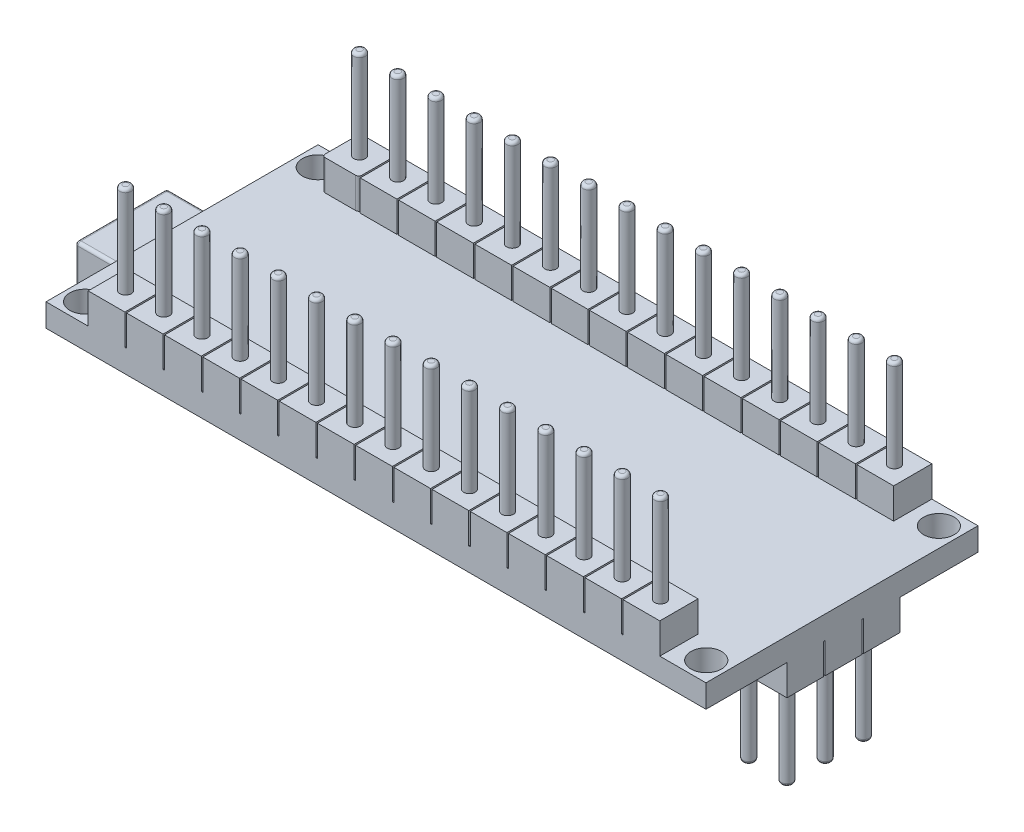
SolidWorks part; units mm, degrees
ref_plane "Front Plane" through (0, 0, 0) normal (0, 0, 1) x (1, 0, 0)
ref_plane "Top Plane" through (0, 0, 0) normal (0, 1, 0) x (1, 0, 0)
ref_plane "Right Plane" through (0, 0, 0) normal (1, 0, 0) x (0, 0, -1)
sketch "Sketch1" plane through (0, 0, 0) normal (0, 1, 0) x (1, 0, 0)
  line L1 (21.59, -8.9) -> (-21.59, -8.9)
  line L2 (21.59, -8.9) -> (21.59, 8.9)
  line L3 (21.59, 8.9) -> (-21.59, 8.9)
  line L4 (-21.59, -8.9) -> (-21.59, 8.9)
  line L5 (21.59, -8.9) -> (-21.59, 8.9) construction
  line L6 (21.59, 8.9) -> (-21.59, -8.9) construction
  point P0 (0, 0)
  dimension "D1" = 17.8
  dimension "D2" = 43.18
extrude "Boss-Extrude1" add sketch "Sketch1" along normal blind 1.5
sketch "Sketch5" plane through (0, 1.5, 0) normal (0, 1, 0) x (1, 0, 0)
  line L0 (21.59, 8.9) -> (-21.59, 8.9) construction
  line L1 (-21.59, 8.9) -> (-21.59, -8.9) construction
  line L2 (0, 8.9) -> (0, -8.9) construction
  line L3 (-21.59, -8.9) -> (21.59, -8.9) construction
  line L4 (21.59, 0) -> (-29.5736, 0) construction
  line L5 (21.59, -8.9) -> (21.59, 8.9) construction
  circle A0 centre (-20.32, 7.61) radius 1
  circle A1 centre (20.32, 7.61) radius 1
  circle A2 centre (20.32, -7.61) radius 1
  circle A3 centre (-20.32, -7.61) radius 1
  dimension "D3" = 2
  dimension "D1" = 1.29
  dimension "D2" = 1.27
extrude "Cut-Extrude2" cut sketch "Sketch5" against normal blind 6
sketch "Sketch6" plane through (0, 1.5, 0) normal (0, 1, 0) x (1, 0, 0)
  line L0 (21.59, 8.9) -> (-21.59, 8.9) construction
  line L1 (-18.83, 8.9) -> (-16.43, 8.9)
  line L2 (-18.83, 8.9) -> (-18.83, 6.4)
  line L3 (-18.83, 6.4) -> (-16.43, 6.4)
  line L4 (-16.43, 8.9) -> (-16.43, 6.4)
  line L5 (-18.83, 8.9) -> (-16.43, 6.4) construction
  line L6 (-18.83, 6.4) -> (-16.43, 8.9) construction
  line L7 (-21.59, 8.9) -> (-21.59, -8.9) construction
  line L8 (-16.33, 8.9) -> (-13.93, 8.9)
  line L9 (-16.33, 8.9) -> (-16.33, 6.4)
  line L10 (-16.33, 6.4) -> (-13.93, 6.4)
  line L11 (-13.93, 8.9) -> (-13.93, 6.4)
  line L12 (-13.83, 8.9) -> (-11.43, 8.9)
  line L13 (-13.83, 8.9) -> (-13.83, 6.4)
  line L14 (-13.83, 6.4) -> (-11.43, 6.4)
  line L15 (-11.43, 8.9) -> (-11.43, 6.4)
  line L16 (-11.33, 8.9) -> (-8.93, 8.9)
  line L17 (-11.33, 8.9) -> (-11.33, 6.4)
  line L18 (-11.33, 6.4) -> (-8.93, 6.4)
  line L19 (-8.93, 8.9) -> (-8.93, 6.4)
  line L20 (-8.83, 8.9) -> (-6.43, 8.9)
  line L21 (-8.83, 8.9) -> (-8.83, 6.4)
  line L22 (-8.83, 6.4) -> (-6.43, 6.4)
  line L23 (-6.43, 8.9) -> (-6.43, 6.4)
  line L24 (-6.33, 8.9) -> (-3.93, 8.9)
  line L25 (-6.33, 8.9) -> (-6.33, 6.4)
  line L26 (-6.33, 6.4) -> (-3.93, 6.4)
  line L27 (-3.93, 8.9) -> (-3.93, 6.4)
  line L28 (-3.83, 8.9) -> (-1.43, 8.9)
  line L29 (-3.83, 8.9) -> (-3.83, 6.4)
  line L30 (-3.83, 6.4) -> (-1.43, 6.4)
  line L31 (-1.43, 8.9) -> (-1.43, 6.4)
  line L32 (-1.33, 8.9) -> (1.07, 8.9)
  line L33 (-1.33, 8.9) -> (-1.33, 6.4)
  line L34 (-1.33, 6.4) -> (1.07, 6.4)
  line L35 (1.07, 8.9) -> (1.07, 6.4)
  line L36 (1.17, 8.9) -> (3.57, 8.9)
  line L37 (1.17, 8.9) -> (1.17, 6.4)
  line L38 (1.17, 6.4) -> (3.57, 6.4)
  line L39 (3.57, 8.9) -> (3.57, 6.4)
  line L40 (3.67, 8.9) -> (6.07, 8.9)
  line L41 (3.67, 8.9) -> (3.67, 6.4)
  line L42 (3.67, 6.4) -> (6.07, 6.4)
  line L43 (6.07, 8.9) -> (6.07, 6.4)
  line L44 (6.17, 8.9) -> (8.57, 8.9)
  line L45 (6.17, 8.9) -> (6.17, 6.4)
  line L46 (6.17, 6.4) -> (8.57, 6.4)
  line L47 (8.57, 8.9) -> (8.57, 6.4)
  line L48 (8.67, 8.9) -> (11.07, 8.9)
  line L49 (8.67, 8.9) -> (8.67, 6.4)
  line L50 (8.67, 6.4) -> (11.07, 6.4)
  line L51 (11.07, 8.9) -> (11.07, 6.4)
  line L52 (11.17, 8.9) -> (13.57, 8.9)
  line L53 (11.17, 8.9) -> (11.17, 6.4)
  line L54 (11.17, 6.4) -> (13.57, 6.4)
  line L55 (13.57, 8.9) -> (13.57, 6.4)
  line L56 (13.67, 8.9) -> (16.07, 8.9)
  line L57 (13.67, 8.9) -> (13.67, 6.4)
  line L58 (13.67, 6.4) -> (16.07, 6.4)
  line L59 (16.07, 8.9) -> (16.07, 6.4)
  line L60 (16.17, 8.9) -> (18.57, 8.9)
  line L61 (16.17, 8.9) -> (16.17, 6.4)
  line L62 (16.17, 6.4) -> (18.57, 6.4)
  line L63 (18.57, 8.9) -> (18.57, 6.4)
  line L64 (0, 0) -> (21.59, 0) construction
  line L65 (21.59, -8.9) -> (21.59, 8.9) construction
  line L66 (-18.83, -6.4) -> (-16.43, -8.9) construction
  line L67 (-18.83, -8.9) -> (-16.43, -6.4) construction
  line L68 (18.57, -8.9) -> (18.57, -6.4)
  line L69 (16.17, -6.4) -> (18.57, -6.4)
  line L70 (16.17, -8.9) -> (16.17, -6.4)
  line L71 (16.17, -8.9) -> (18.57, -8.9)
  line L72 (16.07, -8.9) -> (16.07, -6.4)
  line L73 (13.67, -6.4) -> (16.07, -6.4)
  line L74 (13.67, -8.9) -> (13.67, -6.4)
  line L75 (13.67, -8.9) -> (16.07, -8.9)
  line L76 (13.57, -8.9) -> (13.57, -6.4)
  line L77 (11.17, -6.4) -> (13.57, -6.4)
  line L78 (11.17, -8.9) -> (11.17, -6.4)
  line L79 (11.17, -8.9) -> (13.57, -8.9)
  line L80 (11.07, -8.9) -> (11.07, -6.4)
  line L81 (8.67, -6.4) -> (11.07, -6.4)
  line L82 (8.67, -8.9) -> (8.67, -6.4)
  line L83 (8.67, -8.9) -> (11.07, -8.9)
  line L84 (8.57, -8.9) -> (8.57, -6.4)
  line L85 (6.17, -6.4) -> (8.57, -6.4)
  line L86 (6.17, -8.9) -> (6.17, -6.4)
  line L87 (6.17, -8.9) -> (8.57, -8.9)
  line L88 (6.07, -8.9) -> (6.07, -6.4)
  line L89 (3.67, -6.4) -> (6.07, -6.4)
  line L90 (3.67, -8.9) -> (3.67, -6.4)
  line L91 (3.67, -8.9) -> (6.07, -8.9)
  line L92 (3.57, -8.9) -> (3.57, -6.4)
  line L93 (1.17, -6.4) -> (3.57, -6.4)
  line L94 (1.17, -8.9) -> (1.17, -6.4)
  line L95 (1.17, -8.9) -> (3.57, -8.9)
  line L96 (1.07, -8.9) -> (1.07, -6.4)
  line L97 (-1.33, -6.4) -> (1.07, -6.4)
  line L98 (-1.33, -8.9) -> (-1.33, -6.4)
  line L99 (-1.33, -8.9) -> (1.07, -8.9)
  line L100 (-1.43, -8.9) -> (-1.43, -6.4)
  line L101 (-3.83, -6.4) -> (-1.43, -6.4)
  line L102 (-3.83, -8.9) -> (-3.83, -6.4)
  line L103 (-3.83, -8.9) -> (-1.43, -8.9)
  line L104 (-3.93, -8.9) -> (-3.93, -6.4)
  line L105 (-6.33, -6.4) -> (-3.93, -6.4)
  line L106 (-6.33, -8.9) -> (-6.33, -6.4)
  line L107 (-6.33, -8.9) -> (-3.93, -8.9)
  line L108 (-6.43, -8.9) -> (-6.43, -6.4)
  line L109 (-8.83, -6.4) -> (-6.43, -6.4)
  line L110 (-8.83, -8.9) -> (-8.83, -6.4)
  line L111 (-8.83, -8.9) -> (-6.43, -8.9)
  line L112 (-8.93, -8.9) -> (-8.93, -6.4)
  line L113 (-11.33, -6.4) -> (-8.93, -6.4)
  line L114 (-11.33, -8.9) -> (-11.33, -6.4)
  line L115 (-11.33, -8.9) -> (-8.93, -8.9)
  line L116 (-11.43, -8.9) -> (-11.43, -6.4)
  line L117 (-13.83, -6.4) -> (-11.43, -6.4)
  line L118 (-13.83, -8.9) -> (-13.83, -6.4)
  line L119 (-13.83, -8.9) -> (-11.43, -8.9)
  line L120 (-13.93, -8.9) -> (-13.93, -6.4)
  line L121 (-16.33, -6.4) -> (-13.93, -6.4)
  line L122 (-16.33, -8.9) -> (-16.33, -6.4)
  line L123 (-16.33, -8.9) -> (-13.93, -8.9)
  line L124 (-16.43, -8.9) -> (-16.43, -6.4)
  line L125 (-18.83, -6.4) -> (-16.43, -6.4)
  line L126 (-18.83, -8.9) -> (-18.83, -6.4)
  line L127 (-18.83, -8.9) -> (-16.43, -8.9)
  point P0 (-17.63, 7.65)
  point P130 (-17.63, -7.65)
  dimension "D1" = 2.4
  dimension "D2" = 2.5
  dimension "D3" = 0
  dimension "D4" = 2.76
  dimension "D5" = 15
extrude "Boss-Extrude3" add sketch "Sketch6" along normal blind 2
sketch "Sketch7" plane through (0, 3.5, 0) normal (0, 1, 0) x (1, 0, 0)
  line L0 (-18.83, 8.9) -> (-18.83, 6.4) construction
  line L1 (-16.43, 8.9) -> (-18.83, 8.9) construction
  line L2 (0, 0) -> (21.1488, 0) construction
  circle A0 centre (-17.63, 7.6546) radius 0.375
  circle A1 centre (-15.13, 7.6546) radius 0.375
  circle A2 centre (-12.63, 7.6546) radius 0.375
  circle A3 centre (-10.13, 7.6546) radius 0.375
  circle A4 centre (-7.63, 7.6546) radius 0.375
  circle A5 centre (-5.13, 7.6546) radius 0.375
  circle A6 centre (-2.63, 7.6546) radius 0.375
  circle A7 centre (-0.13, 7.6546) radius 0.375
  circle A8 centre (2.37, 7.6546) radius 0.375
  circle A9 centre (4.87, 7.6546) radius 0.375
  circle A10 centre (7.37, 7.6546) radius 0.375
  circle A11 centre (9.87, 7.6546) radius 0.375
  circle A12 centre (12.37, 7.6546) radius 0.375
  circle A13 centre (14.87, 7.6546) radius 0.375
  circle A14 centre (17.37, 7.6546) radius 0.375
  circle A15 centre (17.37, -7.6546) radius 0.375
  circle A16 centre (14.87, -7.6546) radius 0.375
  circle A17 centre (12.37, -7.6546) radius 0.375
  circle A18 centre (9.87, -7.6546) radius 0.375
  circle A19 centre (7.37, -7.6546) radius 0.375
  circle A20 centre (4.87, -7.6546) radius 0.375
  circle A21 centre (2.37, -7.6546) radius 0.375
  circle A22 centre (-0.13, -7.6546) radius 0.375
  circle A23 centre (-2.63, -7.6546) radius 0.375
  circle A24 centre (-5.13, -7.6546) radius 0.375
  circle A25 centre (-7.63, -7.6546) radius 0.375
  circle A26 centre (-10.13, -7.6546) radius 0.375
  circle A27 centre (-12.63, -7.6546) radius 0.375
  circle A28 centre (-15.13, -7.6546) radius 0.375
  circle A29 centre (-17.63, -7.6546) radius 0.375
  point P2 (-18.83, 7.65)
  dimension "D1" = 0.75
  dimension "D3" = 1.2454
  dimension "D2" = 1.2
  dimension "D4" = 15
extrude "Boss-Extrude4" add sketch "Sketch7" along normal blind 6
fillet "Fillet5" radius 0.2 30 edges at (-15.13, 9.5, 7.2796) (-5.13, 9.5, -7.2796) (-7.63, 9.5, -7.2796) (-17.63, 9.5, 7.2796) (-12.63, 9.5, 7.2796) (-10.13, 9.5, 7.2796) (-7.63, 9.5, 7.2796) (-5.13, 9.5, 7.2796) (-2.63, 9.5, 7.2796) (-0.13, 9.5, 7.2796) (2.37, 9.5, 7.2796) (4.87, 9.5, 7.2796) (7.37, 9.5, 7.2796) (9.87, 9.5, 7.2796) (12.37, 9.5, 7.2796) (14.87, 9.5, 7.2796) (17.37, 9.5, 7.2796) (17.37, 9.5, -7.2796) (14.87, 9.5, -7.2796) (12.37, 9.5, -7.2796) (9.87, 9.5, -7.2796) (7.37, 9.5, -7.2796) (4.87, 9.5, -7.2796) (2.37, 9.5, -7.2796) (-0.13, 9.5, -7.2796) (-2.63, 9.5, -7.2796) (-10.13, 9.5, -7.2796) (-12.63, 9.5, -7.2796) (-15.13, 9.5, -7.2796) (-17.63, 9.5, -7.2796)
sketch "Sketch8" plane through (0, 0, 0) normal (0, -1, 0) x (1, 0, 0)
  line L0 (-21.59, -8.9) -> (-21.59, 8.9) construction
  line L1 (-17.59, -3) -> (-25.59, -3)
  line L2 (-17.59, -3) -> (-17.59, 3)
  line L3 (-17.59, 3) -> (-25.59, 3)
  line L4 (-25.59, -3) -> (-25.59, 3)
  line L5 (-17.59, -3) -> (-25.59, 3) construction
  line L6 (-17.59, 3) -> (-25.59, -3) construction
  point P0 (-21.59, 0)
  dimension "D1" = 6
  dimension "D2" = 8
extrude "Boss-Extrude5" add sketch "Sketch8" along normal blind 6
sketch "Sketch9" plane through (-25.59, 0, 0) normal (-1, 0, 0) x (0, 0, 1)
  line L0 (2.5, -0.5) -> (-2.5, -0.5)
  line L1 (-2.5, -0.5) -> (-2.5, -5.5)
  line L2 (-2.5, -5.5) -> (2.5, -5.5)
  line L3 (2.5, -5.5) -> (2.5, -0.5)
  line L4 (3, 0) -> (-3, 0)
  line L5 (-3, 0) -> (-3, -6)
  line L6 (-3, -6) -> (3, -6)
  line L7 (3, -6) -> (3, 0)
  line L8 (3, 0) -> (-3, 0)
  line L9 (-3, 0) -> (-3, -6)
  line L10 (-3, -6) -> (3, -6)
  line L11 (3, -6) -> (3, 0)
  dimension "D1" = 0
  dimension "D2" = 0.5
extrude "Cut-Extrude3" cut sketch "Sketch9" against normal blind 6 contours L2 L3 L0 L1
fillet "Fillet6" radius 0.2 15 edges at (-25.59, -3, 3) (-25.59, -6, 0) (-25.59, -3, -3) (-25.59, 0, 0) (-25.59, -0.5, 0) (-25.59, -3, -2.5) (-25.59, -5.5, 0) (-25.59, -3, 2.5) (-17.59, -3, 3) (-17.59, -3, -3) (-17.59, -6, 0) (-21.59, -6, -3) (-21.59, -6, 3) (-23.59, 0, -3) (-23.59, 0, 3)
sketch "Sketch10" plane through (0, 0, 0) normal (0, -1, 0) x (1, 0, 0)
  line L0 (21.59, -8.9) -> (-21.59, -8.9) construction
  line L1 (21.59, -3.8) -> (19.19, -3.8)
  line L2 (21.59, -3.8) -> (21.59, -1.4)
  line L3 (21.59, -1.4) -> (19.19, -1.4)
  line L4 (19.19, -3.8) -> (19.19, -1.4)
  line L5 (21.59, -3.8) -> (19.19, -1.4) construction
  line L6 (21.59, -1.4) -> (19.19, -3.8) construction
  line L7 (21.59, 8.9) -> (21.59, -8.9) construction
  line L8 (19.09, -1.4) -> (16.69, -1.4)
  line L9 (16.69, -3.8) -> (16.69, -1.4)
  line L10 (19.09, -3.8) -> (16.69, -3.8)
  line L11 (19.09, -3.8) -> (19.09, -1.4)
  line L12 (19.09, 1.1) -> (16.69, 1.1)
  line L13 (16.69, -1.3) -> (16.69, 1.1)
  line L14 (19.09, -1.3) -> (16.69, -1.3)
  line L15 (19.09, -1.3) -> (19.09, 1.1)
  line L16 (19.09, 3.6) -> (16.69, 3.6)
  line L17 (16.69, 1.2) -> (16.69, 3.6)
  line L18 (19.09, 1.2) -> (16.69, 1.2)
  line L19 (19.09, 1.2) -> (19.09, 3.6)
  line L20 (21.59, 1.1) -> (19.19, 1.1)
  line L21 (19.19, -1.3) -> (19.19, 1.1)
  line L22 (21.59, -1.3) -> (19.19, -1.3)
  line L23 (21.59, -1.3) -> (21.59, 1.1)
  line L24 (21.59, 3.6) -> (19.19, 3.6)
  line L25 (19.19, 1.2) -> (19.19, 3.6)
  line L26 (21.59, 1.2) -> (19.19, 1.2)
  line L27 (21.59, 1.2) -> (21.59, 3.6)
  point P0 (20.39, -2.6)
  dimension "D1" = 2.4
  dimension "D2" = 2.4
  dimension "D3" = 5.1
  dimension "D4" = 0
  dimension "D5" = 2
  dimension "D6" = 3
extrude "Boss-Extrude6" add sketch "Sketch10" along normal blind 2
sketch "Sketch11" plane through (0, -2, 0) normal (0, -1, 0) x (1, 0, 0)
  line L0 (19.19, -3.8) -> (21.59, -3.8) construction
  line L1 (21.59, -3.8) -> (21.59, -1.4) construction
  circle A0 centre (20.39, -2.6) radius 0.375
  circle A1 centre (17.89, -2.6) radius 0.375
  circle A2 centre (17.89, -0.1) radius 0.375
  circle A3 centre (17.89, 2.4) radius 0.375
  circle A4 centre (20.39, -0.1) radius 0.375
  circle A5 centre (20.39, 2.4) radius 0.375
  dimension "D1" = 0.75
  dimension "D2" = 1.2
  dimension "D3" = 1.2
  dimension "D4" = 2
  dimension "D5" = 3
extrude "Boss-Extrude7" add sketch "Sketch11" along normal blind 6
fillet "Fillet7" radius 0.2 6 edges at (17.89, -8, -2.975) (20.39, -8, -2.975) (20.39, -8, -0.475) (17.89, -8, -0.475) (17.89, -8, 2.025) (20.39, -8, 2.025)
fillet "Fillet4" radius 0.2 4 edges at (-16.43, 2.5, -6.4) (-18.83, 2.5, -6.4)
